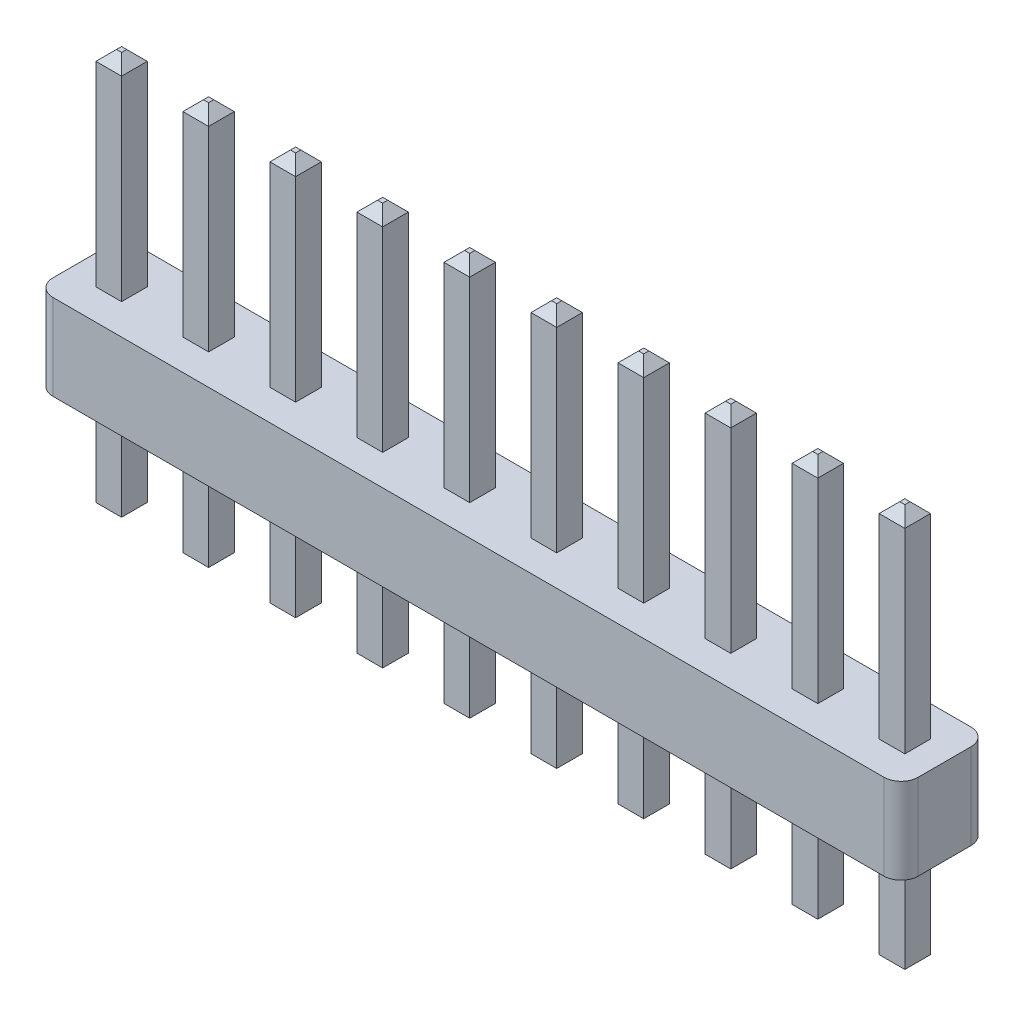
SolidWorks part; units mm, degrees
ref_plane "Front Plane" through (0, 0, 0) normal (0, 0, 1) x (1, 0, 0)
ref_plane "Top Plane" through (0, 0, 0) normal (0, 1, 0) x (1, 0, 0)
ref_plane "Right Plane" through (0, 0, 0) normal (1, 0, 0) x (0, 0, -1)
ref_plane "Plane1" through (0, 0, 0) normal (0, 1, 0) x (-1, 0, 0)
sketch "Sketch1" plane through (0, 0, 0) normal (0, 1, 0) x (-1, 0, 0)
  line L0 (-22.25, 1.27) -> (2, 1.27)
  line L1 (2.5, 0.77) -> (2.5, -0.77)
  line L2 (2, -1.27) -> (-22.25, -1.27)
  line L3 (-22.75, -0.77) -> (-22.75, 0.77)
  line L4 (0, 55) -> (0, -55) construction
  line L5 (55, 0) -> (-55, 0) construction
  arc A0 (2.5, 0.77) -> (2, 1.27) centre (2, 0.77) ccw
  arc A1 (2, -1.27) -> (2.5, -0.77) centre (2, -0.77) ccw
  arc A2 (-22.75, -0.77) -> (-22.25, -1.27) centre (-22.25, -0.77) ccw
  arc A3 (-22.25, 1.27) -> (-22.75, 0.77) centre (-22.25, 0.77) ccw
  dimension "D5" = 0.5
  dimension "D1" = 25.25
  dimension "D2" = 2.54
  dimension "D3" = 2.5
  dimension "D4" = 1.27
extrude "Boss-Extrude1" add sketch "Sketch1" along normal blind 2.5
ref_plane "Plane2" through (0, 0, 0) normal (0, 1, 0) x (-1, 0, 0)
sketch "Sketch2" plane through (0, 0, 0) normal (0, 1, 0) x (-1, 0, 0)
  line L0 (0.895, 0.375) -> (1.645, 0.375)
  line L1 (1.645, 0.375) -> (1.645, -0.375)
  line L2 (1.645, -0.375) -> (0.895, -0.375)
  line L3 (0.895, -0.375) -> (0.895, 0.375)
  line L4 (-0.895, -0.375) -> (-1.645, -0.375)
  line L5 (-1.645, -0.375) -> (-1.645, 0.375)
  line L6 (-1.645, 0.375) -> (-0.895, 0.375)
  line L7 (-0.895, 0.375) -> (-0.895, -0.375)
  line L8 (-1.645, 0.375) -> (-0.895, -0.375) construction
  line L9 (0.895, -0.375) -> (1.645, 0.375) construction
  line L10 (1.375, 0) -> (-1.375, 0) construction
  line L11 (0, 1.375) -> (0, -1.375) construction
  line L12 (-4.185, 0.375) -> (-3.435, 0.375)
  line L13 (-3.435, 0.375) -> (-3.435, -0.375)
  line L14 (-3.435, -0.375) -> (-4.185, -0.375)
  line L15 (-4.185, -0.375) -> (-4.185, 0.375)
  line L16 (-5.975, -0.375) -> (-6.725, -0.375)
  line L17 (-6.725, -0.375) -> (-6.725, 0.375)
  line L18 (-6.725, 0.375) -> (-5.975, 0.375)
  line L19 (-5.975, 0.375) -> (-5.975, -0.375)
  line L20 (-6.725, 0.375) -> (-5.975, -0.375) construction
  line L21 (-4.185, -0.375) -> (-3.435, 0.375) construction
  line L22 (-9.265, 0.375) -> (-8.515, 0.375)
  line L23 (-8.515, 0.375) -> (-8.515, -0.375)
  line L24 (-8.515, -0.375) -> (-9.265, -0.375)
  line L25 (-9.265, -0.375) -> (-9.265, 0.375)
  line L26 (-11.055, -0.375) -> (-11.805, -0.375)
  line L27 (-11.805, -0.375) -> (-11.805, 0.375)
  line L28 (-11.805, 0.375) -> (-11.055, 0.375)
  line L29 (-11.055, 0.375) -> (-11.055, -0.375)
  line L30 (-11.805, 0.375) -> (-11.055, -0.375) construction
  line L31 (-9.265, -0.375) -> (-8.515, 0.375) construction
  line L32 (-14.345, 0.375) -> (-13.595, 0.375)
  line L33 (-13.595, 0.375) -> (-13.595, -0.375)
  line L34 (-13.595, -0.375) -> (-14.345, -0.375)
  line L35 (-14.345, -0.375) -> (-14.345, 0.375)
  line L36 (-16.135, -0.375) -> (-16.885, -0.375)
  line L37 (-16.885, -0.375) -> (-16.885, 0.375)
  line L38 (-16.885, 0.375) -> (-16.135, 0.375)
  line L39 (-16.135, 0.375) -> (-16.135, -0.375)
  line L40 (-16.885, 0.375) -> (-16.135, -0.375) construction
  line L41 (-14.345, -0.375) -> (-13.595, 0.375) construction
  line L42 (-19.425, 0.375) -> (-18.675, 0.375)
  line L43 (-18.675, 0.375) -> (-18.675, -0.375)
  line L44 (-18.675, -0.375) -> (-19.425, -0.375)
  line L45 (-19.425, -0.375) -> (-19.425, 0.375)
  line L46 (-21.215, -0.375) -> (-21.965, -0.375)
  line L47 (-21.965, -0.375) -> (-21.965, 0.375)
  line L48 (-21.965, 0.375) -> (-21.215, 0.375)
  line L49 (-21.215, 0.375) -> (-21.215, -0.375)
  line L50 (-21.965, 0.375) -> (-21.215, -0.375) construction
  line L51 (-19.425, -0.375) -> (-18.675, 0.375) construction
  point P8 (-1.27, 0)
  point P9 (1.27, 0)
  point P24 (-6.35, 0)
  point P25 (-3.81, 0)
  point P34 (-11.43, 0)
  point P35 (-8.89, 0)
  point P44 (-16.51, 0)
  point P45 (-13.97, 0)
  point P54 (-21.59, 0)
  point P55 (-19.05, 0)
  dimension "D1" = 2.54
  dimension "D2" = 0.75
  dimension "D3" = 1.27
  dimension "D4" = 5
extrude "Boss-Extrude2" add sketch "Sketch2" along normal blind 8.5 and the other way blind 3.25
chamfer "Chamfer1" distance 0.3 angle 45 80 edges at (-1.645, 8.5, 0) (-1.27, 8.5, -0.375) (-0.895, 8.5, 0) (-1.27, 8.5, 0.375) (0.895, 8.5, 0) (1.27, 8.5, -0.375) (1.645, 8.5, 0) (1.27, 8.5, 0.375) (1.27, -3.25, -0.375) (1.645, -3.25, 0) (0.895, -3.25, 0) (1.27, -3.25, 0.375) (-1.27, -3.25, 0.375) (-1.645, -3.25, 0) (-0.895, -3.25, 0) (-1.27, -3.25, -0.375) (21.59, -3.25, 0.375) (21.965, -3.25, 0) (21.59, -3.25, -0.375) (21.215, -3.25, 0) (19.05, -3.25, -0.375) (18.675, -3.25, 0) (19.05, -3.25, 0.375) (19.425, -3.25, 0) (16.51, -3.25, 0.375) (16.885, -3.25, 0) (16.51, -3.25, -0.375) (16.135, -3.25, 0) (13.97, -3.25, -0.375) (13.595, -3.25, 0) (13.97, -3.25, 0.375) (14.345, -3.25, 0) (11.43, -3.25, 0.375) (11.805, -3.25, 0) (11.43, -3.25, -0.375) (11.055, -3.25, 0) (8.89, -3.25, -0.375) (8.515, -3.25, 0) (8.89, -3.25, 0.375) (9.265, -3.25, 0) (6.35, -3.25, 0.375) (6.725, -3.25, 0) (6.35, -3.25, -0.375) (5.975, -3.25, 0) (3.81, -3.25, -0.375) (3.435, -3.25, 0) (3.81, -3.25, 0.375) (4.185, -3.25, 0) (21.59, 8.5, -0.375) (21.965, 8.5, 0) (21.59, 8.5, 0.375) (21.215, 8.5, 0) (19.05, 8.5, 0.375) (18.675, 8.5, 0) (19.05, 8.5, -0.375) (19.425, 8.5, 0) (16.51, 8.5, -0.375) (16.885, 8.5, 0) (16.51, 8.5, 0.375) (16.135, 8.5, 0) (13.97, 8.5, 0.375) (13.595, 8.5, 0) (13.97, 8.5, -0.375) (14.345, 8.5, 0) (11.43, 8.5, -0.375) (11.805, 8.5, 0) (11.43, 8.5, 0.375) (11.055, 8.5, 0) (8.89, 8.5, 0.375) (8.515, 8.5, 0) (8.89, 8.5, -0.375) (9.265, 8.5, 0) (6.35, 8.5, -0.375) (6.725, 8.5, 0) (6.35, 8.5, 0.375) (5.975, 8.5, 0) (3.81, 8.5, 0.375) (3.435, 8.5, 0) (3.81, 8.5, -0.375) (4.185, 8.5, 0)
